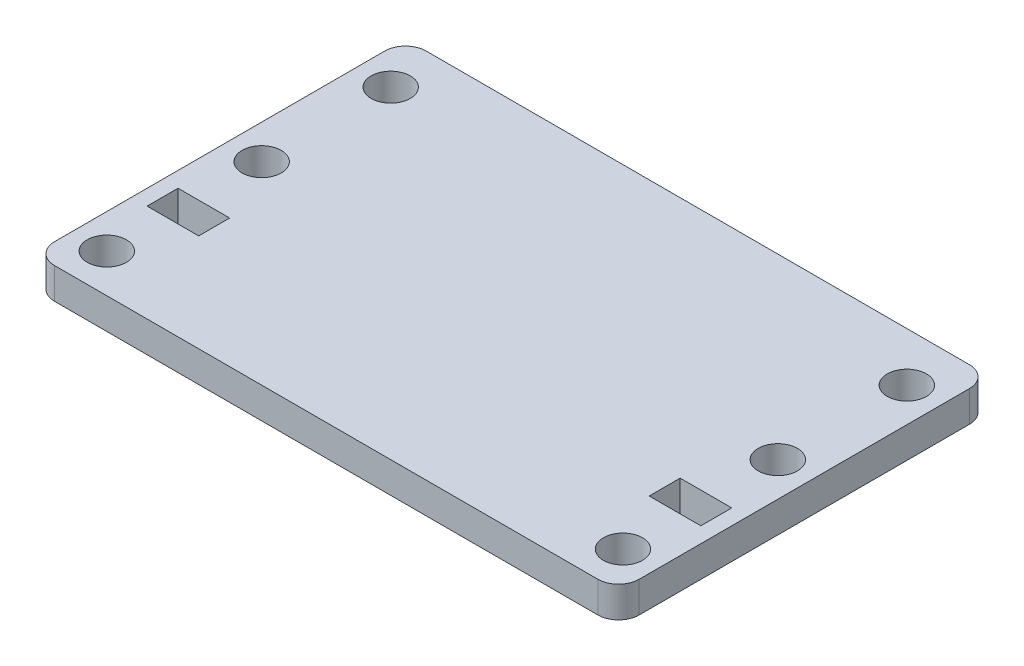
SolidWorks part; units mm, degrees
material "Acrylic (Medium-high impact)"
ref_plane "Front Plane" through (0, 0, 0) normal (0, 0, 1) x (1, 0, 0)
ref_plane "Top Plane" through (0, 0, 0) normal (0, 1, 0) x (1, 0, 0)
ref_plane "Right Plane" through (0, 0, 0) normal (1, 0, 0) x (0, 0, -1)
sketch "Sketch1" plane through (0, 0, 0) normal (0, 1, 0) x (1, 0, 0)
  line L1 (0, 36) -> (-56.64, 36)
  line L2 (0, 36) -> (0, 0)
  line L3 (0, 0) -> (-56.64, 0)
  line L4 (-56.64, 36) -> (-56.64, 0)
  dimension "D1" = 36
  dimension "D2" = 56.64
extrude "Boss-Extrude1" add sketch "Sketch1" along normal blind 3
hole_wizard "#6 Clearance Hole2" positions "Sketch5" profile "Sketch6" hole size "#6" standard "ANSI Inch" end condition through all
sketch "Sketch5" plane through (0, 3, 0) normal (0, 1, 0) x (1, 0, 0)
  line L7 (-56.64, 36) -> (-56.64, 0) construction
  line L8 (-56.64, 0) -> (0, 0) construction
  point P0 (-53.32, 31.25)
  point P2 (-53.32, 18.75)
  point P4 (-53.32, 3.75)
  point P6 (-3.32, 31.25)
  point P8 (-3.32, 18.75)
  point P10 (-3.32, 3.75)
  dimension "D1" = 15
  dimension "D2" = 27.5
  dimension "D4" = 50
  dimension "D3" = 3.32
  dimension "D5" = 3.75
sketch "Sketch6" plane through (-53.32, 3, -31.25) normal (1, 0, 0) x (0, 0, 1)
  line L0 (0, 0) -> (0, 3)
  line L1 (0, 3) -> (1.8986, 3)
  line L2 (1.8986, 3) -> (1.8986, 0)
  line L5 (1.8986, 0) -> (0, 0)
  line L11 (0, -6.35) -> (0, 107.95) construction
  dimension "Thru Hole Dia." = 3.7973
  dimension "Thru Hole Depth" = 3
sketch "Sketch7" plane through (0, 3, 0) normal (0, 1, 0) x (1, 0, 0)
  line L0 (-56.64, 36) -> (-56.64, 0) construction
  line L1 (-55.14, 12.47) -> (-50.14, 12.47)
  line L2 (-55.14, 12.47) -> (-55.14, 9.47)
  line L3 (-55.14, 9.47) -> (-50.14, 9.47)
  line L4 (-50.14, 12.47) -> (-50.14, 9.47)
  line L5 (-6.5, 12.47) -> (-1.5, 12.47)
  line L6 (-6.5, 12.47) -> (-6.5, 9.47)
  line L7 (-6.5, 9.47) -> (-1.5, 9.47)
  line L8 (-1.5, 12.47) -> (-1.5, 9.47)
  line L9 (0, 0) -> (0, 36) construction
  line L10 (-56.64, 0) -> (0, 0) construction
  dimension "D1" = 5
  dimension "D2" = 3
  dimension "D3" = 1.5
  dimension "D4" = 1.5
  dimension "D5" = 9.47
extrude "Cut-Extrude1" cut sketch "Sketch7" against normal blind 10
fillet "Fillet1" radius 2 4 edges at (-56.64, 1.5, -36) (0, 1.5, -36) (0, 1.5, 0) (-56.64, 1.5, 0)
equation "\"D3@Sketch5\"=(56.64-\"D4@Sketch5\")/2"
equation "\"D4@Sketch7\"=\"D3@Sketch7\""
